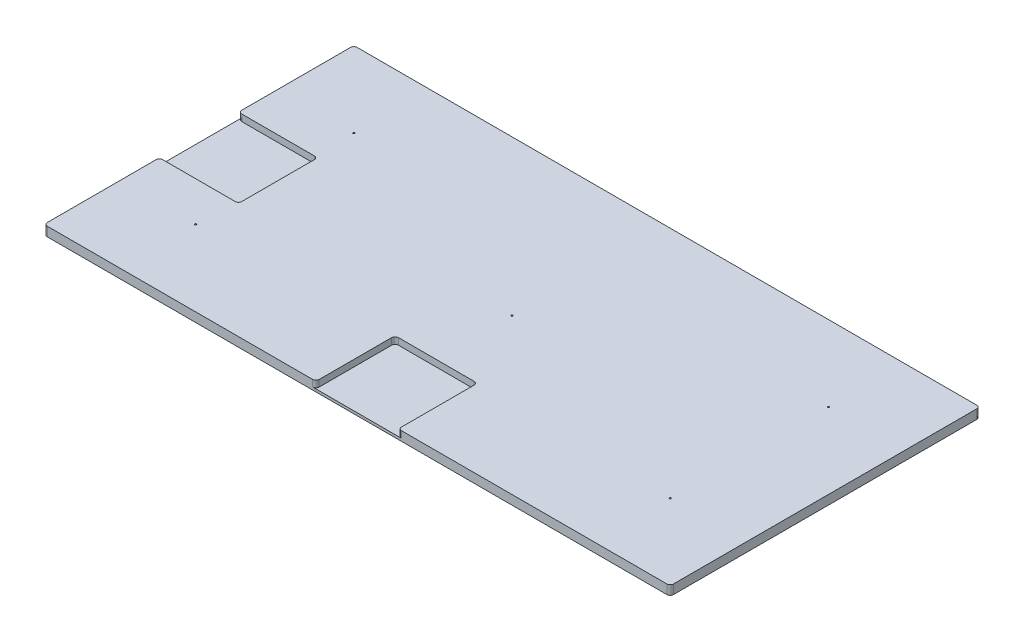
SolidWorks part; units mm, degrees
ref_plane "Front Plane" through (0, 0, 0) normal (0, 0, 1) x (1, 0, 0)
ref_plane "Top Plane" through (0, 0, 0) normal (0, 1, 0) x (1, 0, 0)
ref_plane "Right Plane" through (0, 0, 0) normal (1, 0, 0) x (0, 0, -1)
sketch "Sketch1" plane through (0, 0, 0) normal (0, 1, 0) x (1, 0, 0)
  line L1 (-603.25, -298.45) -> (603.25, -298.45)
  line L2 (-603.25, -298.45) -> (-603.25, 298.45)
  line L3 (-603.25, 298.45) -> (603.25, 298.45)
  line L4 (603.25, -298.45) -> (603.25, 298.45)
  line L5 (-603.25, -298.45) -> (603.25, 298.45) construction
  line L6 (-603.25, 298.45) -> (603.25, -298.45) construction
  point P0 (0, 0)
  dimension "D1" = 1206.5
  dimension "D2" = 596.9
extrude "Boss-Extrude1" add sketch "Sketch1" along normal blind 17.78
hole_wizard "1/8 (0.125) Diameter Hole1" positions "Sketch2" profile "Sketch3" hole size "1/8" standard "ANSI Inch" end condition through all
sketch "Sketch2" plane through (0, 17.78, 0) normal (0, 1, 0) x (1, 0, 0)
  line L1 (-457.2, -152.4) -> (457.2, -152.4) construction
  line L2 (-457.2, -152.4) -> (-457.2, 152.4) construction
  line L3 (-457.2, 152.4) -> (457.2, 152.4) construction
  line L4 (457.2, -152.4) -> (457.2, 152.4) construction
  line L5 (-457.2, -152.4) -> (457.2, 152.4) construction
  line L6 (-457.2, 152.4) -> (457.2, -152.4) construction
  point P0 (0, 0)
  point P1 (457.2, 152.4)
  point P50 (-457.2, -152.4)
  point P51 (-457.2, 152.4)
  point P52 (457.2, -152.4)
  point P63 (0, 0)
  dimension "D1" = 914.4
  dimension "D2" = 304.8
sketch "Sketch3" plane through (0, 17.78, 0) normal (1, 0, 0) x (0, 0, 1)
  line L0 (0, 0) -> (0, 17.78)
  line L1 (0, 17.78) -> (1.5875, 17.78)
  line L2 (1.5875, 17.78) -> (1.5875, 0)
  line L5 (1.5875, 0) -> (0, 0)
  line L11 (0, -6.35) -> (0, 107.95) construction
  dimension "Thru Hole Dia." = 3.175
  dimension "Thru Hole Depth" = 17.78
fillet "Fillet1" radius 6.35 4 edges at (603.25, 8.89, -298.45) (603.25, 8.89, 298.45) (-603.25, 8.89, 298.45) (-603.25, 8.89, -298.45)
sketch "Sketch4" plane through (0, 17.78, 0) normal (0, 1, 0) x (1, 0, 0)
  line L0 (0, 298.45) -> (0, -298.45) construction
  line L1 (596.9, 298.45) -> (-596.9, 298.45) construction
  line L2 (-596.9, -298.45) -> (596.9, -298.45) construction
  line L3 (-603.25, 0) -> (603.25, 0) construction
  line L4 (-79.375, -146.05) -> (79.375, -146.05)
  line L5 (-79.375, -146.05) -> (-79.375, -298.45)
  line L6 (-79.375, -298.45) -> (79.375, -298.45)
  line L7 (79.375, -146.05) -> (79.375, -298.45)
  line L8 (-79.375, -146.05) -> (79.375, -298.45) construction
  line L9 (-79.375, -298.45) -> (79.375, -146.05) construction
  line L10 (-603.25, 292.1) -> (-603.25, -292.1) construction
  line L11 (603.25, -292.1) -> (603.25, 292.1) construction
  line L13 (-450.85, 76.2) -> (-603.25, 76.2)
  line L14 (-450.85, 76.2) -> (-450.85, -76.2)
  line L15 (-450.85, -76.2) -> (-603.25, -76.2)
  line L16 (-603.25, 76.2) -> (-603.25, -76.2)
  line L17 (-450.85, 76.2) -> (-603.25, -76.2) construction
  line L18 (-450.85, -76.2) -> (-603.25, 76.2) construction
  point P6 (0, -222.25)
  point P17 (-527.05, 0)
  dimension "D1" = 158.75
  dimension "D2" = 152.4
  dimension "D3" = 152.4
  dimension "D4" = 152.4
extrude "Cut-Extrude1" cut sketch "Sketch4" against normal blind 12.7
fillet "Fillet2" radius 6.35 8 edges at (79.375, 11.43, 298.45) (-79.375, 11.43, 298.45) (-79.375, 11.43, 146.05) (79.375, 11.43, 146.05) (-603.25, 11.43, 76.2) (-603.25, 11.43, -76.2) (-450.85, 11.43, 76.2) (-450.85, 11.43, -76.2)
